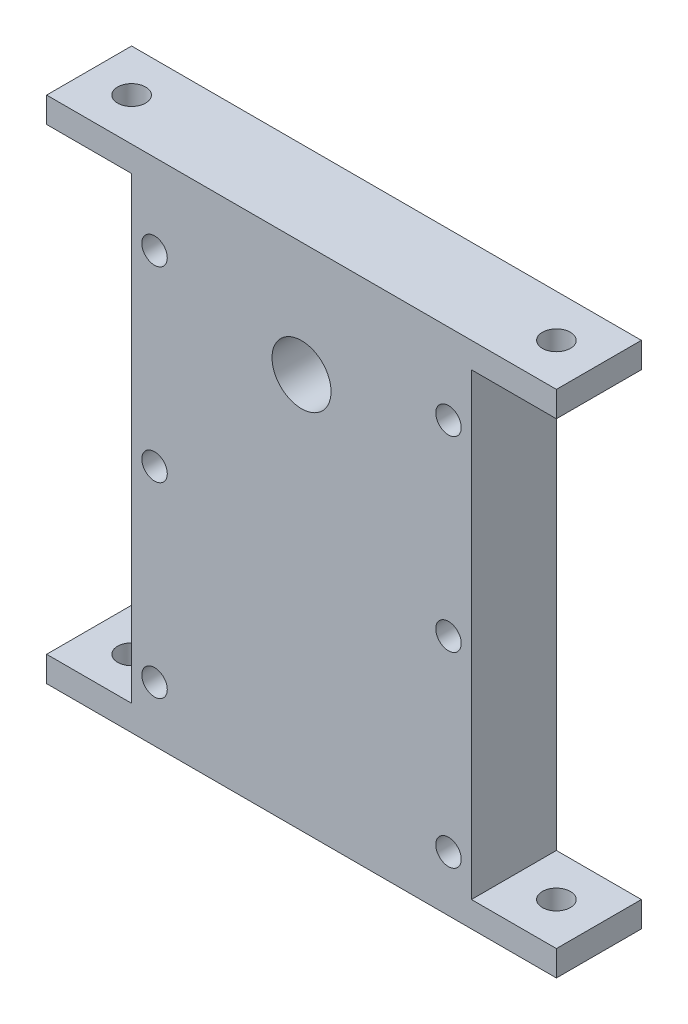
SolidWorks part; units mm, degrees
ref_plane "Front Plane" through (0, 0, 0) normal (0, 0, 1) x (1, 0, 0)
ref_plane "Top Plane" through (0, 0, 0) normal (0, 1, 0) x (1, 0, 0)
ref_plane "Right Plane" through (0, 0, 0) normal (1, 0, 0) x (0, 0, -1)
sketch "Sketch1" plane through (0, 0, 0) normal (0, 0, 1) x (1, 0, 0)
  line L1 (-20, 30) -> (20, 30)
  line L2 (-20, 30) -> (-20, -30)
  line L3 (-20, -30) -> (20, -30)
  line L4 (20, 30) -> (20, -30)
  line L5 (0, -33) -> (0, 33) construction
  circle A0 centre (0, 16.5) radius 3.475
  circle A1 centre (-17.3, -1.5) radius 1.5
  circle A2 centre (-17.3, 20.5) radius 1.5
  circle A3 centre (17.3, -1.5) radius 1.5
  circle A4 centre (17.3, 20.5) radius 1.5
  circle A5 centre (-17.3, -23.5) radius 1.5
  circle A6 centre (17.3, -23.5) radius 1.5
  point P0 (0, 0)
  dimension "D4" = 6.95
  dimension "D10" = 3
  dimension "D11" = 3
  dimension "D12" = 3
  dimension "D1" = 40
  dimension "D2" = 60
  dimension "D3" = 46.5
  dimension "D5" = 30
  dimension "D6" = 20
  dimension "D7" = 28.5
  dimension "D8" = 17.3
  dimension "D9" = 22
  dimension "D13" = 22
extrude "Boss-Extrude1" add sketch "Sketch1" along normal blind 10
sketch "Esquisse1" plane through (20, 0, 0) normal (1, 0, 0) x (0, 0, -1)
  line L0 (0, 30) -> (-10, 30)
  line L1 (-10, 30) -> (-10, 27)
  line L2 (-10, -30) -> (-10, 30) construction
  line L3 (-10, 27) -> (0, 27)
  line L4 (0, -30) -> (0, 30) construction
  line L5 (0, 27) -> (0, 30)
  line L6 (0, -30) -> (0, -27)
  line L7 (0, -27) -> (-10, -27)
  line L8 (-10, -27) -> (-10, -30)
  line L9 (-10, -30) -> (0, -30)
  dimension "D1" = 3
  dimension "D2" = 3
extrude "Boss.-Extru.1" add sketch "Esquisse1" along normal blind 10
sketch "Esquisse2" plane through (-20, 0, 0) normal (-1, 0, 0) x (0, 0, 1)
  line L0 (0, 30) -> (10, 30)
  line L1 (10, 30) -> (10, 27)
  line L2 (10, 27) -> (0, 27)
  line L3 (0, 30) -> (0, -30) construction
  line L4 (0, 27) -> (0, 30)
  line L5 (10, 30) -> (10, -30) construction
  line L6 (0, -30) -> (10, -30)
  line L7 (0, -30) -> (0, -27)
  line L8 (0, -27) -> (10, -27)
  line L9 (10, -30) -> (10, -27)
  dimension "D1" = 3
  dimension "D2" = 3
extrude "Boss.-Extru.2" add sketch "Esquisse2" along normal blind 10
sketch "Esquisse3" plane through (0, 27, 0) normal (0, -1, 0) x (1, 0, 0)
  line L0 (0, -5.5) -> (0, 5.5) construction
  circle A0 centre (-25, 5) radius 1.65
  circle A1 centre (25, 5) radius 1.65
  dimension "D3" = 3.3
  dimension "D1" = 5
  dimension "D2" = 5
extrude "Enlèv. mat.-Extru.1" cut sketch "Esquisse3" against normal through all both and the other way through all
